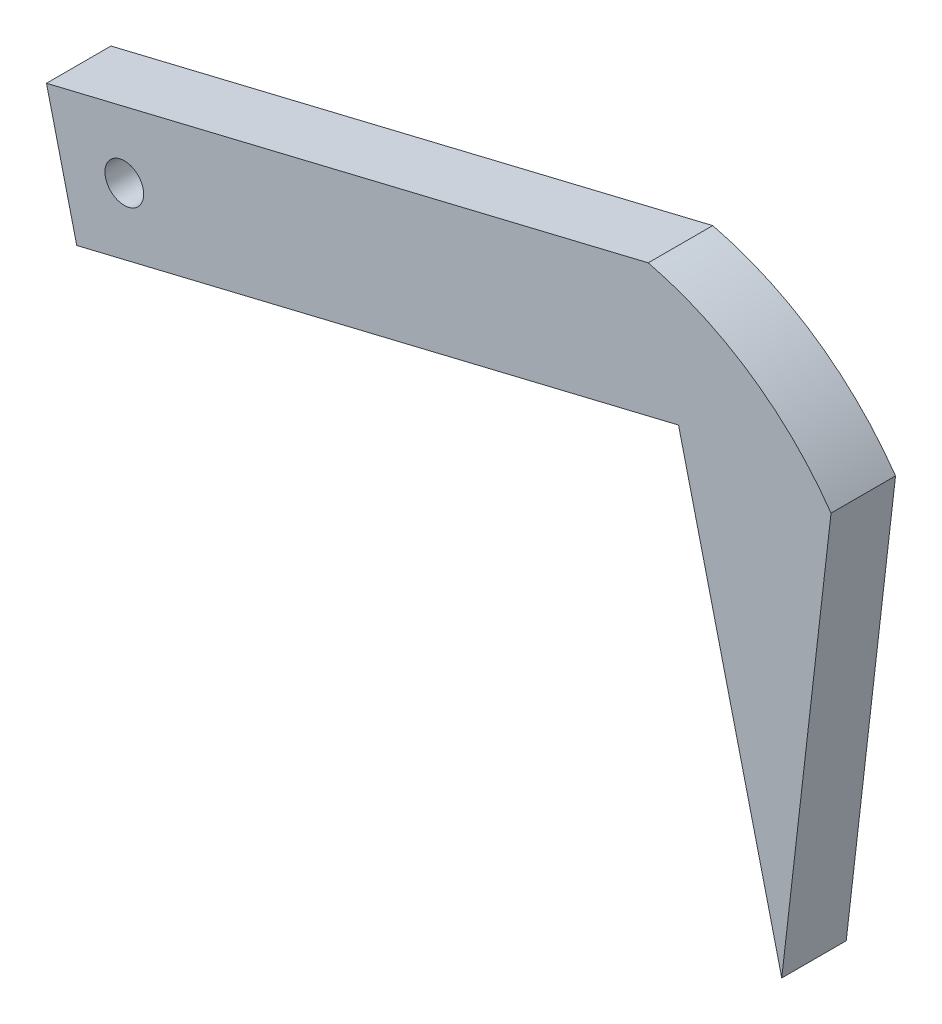
SolidWorks part; units mm, degrees
ref_plane "Plan de face" through (0, 0, 0) normal (0, 0, 1) x (1, 0, 0)
ref_plane "Plan de dessus" through (0, 0, 0) normal (0, 1, 0) x (1, 0, 0)
ref_plane "Plan de droite" through (0, 0, 0) normal (1, 0, 0) x (0, 0, -1)
sketch "Esquisse1" plane through (0, 0, 0) normal (0, 0, 1) x (1, 0, 0)
  line L1 (60.8306, 1.5505) -> (57.0082, -31.5756)
  line L3 (49.0061, 1.5505) -> (2.3481, -9.7204)
  line L4 (2.3481, -9.7204) -> (0, 0)
  line L5 (0, 0) -> (46.658, 11.2709)
  line L6 (49.0061, 1.5505) -> (57.0082, -31.5756)
  arc A0 (46.658, 11.2709) -> (60.8306, 1.5505) centre (40.8933, -12.3264) cw
  circle A1 centre (6.0343, -3.6862) radius 1.5
  point P18 (1.1741, -4.8602)
  dimension "D5" = 3
  dimension "D1" = 10
  dimension "D2" = 60
  dimension "D3" = 48
  dimension "D4" = 48
  dimension "D6" = 5
  dimension "D7" = 5
extrude "Boss.-Extru.1" add sketch "Esquisse1" along normal blind 5
